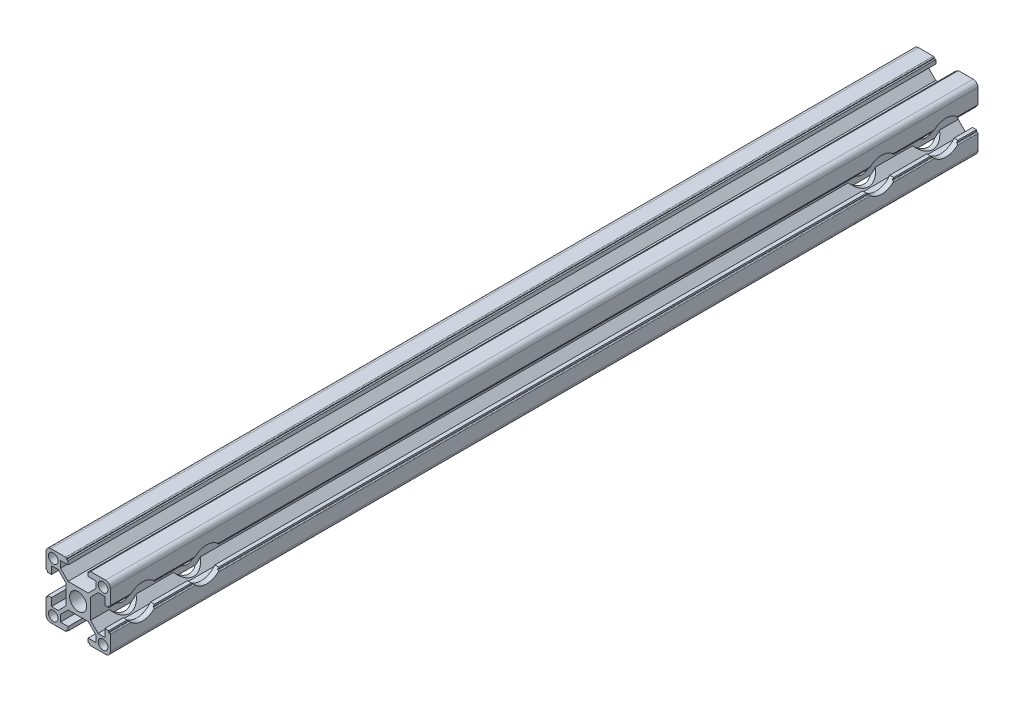
SolidWorks part; units mm, degrees
ref_plane "前视基准面" through (0, 0, 0) normal (0, 0, 1) x (1, 0, 0)
ref_plane "上视基准面" through (0, 0, 0) normal (0, 1, 0) x (1, 0, 0)
ref_plane "右视基准面" through (0, 0, 0) normal (1, 0, 0) x (0, 0, -1)
sketch "草图1" plane through (0, 0, 0) normal (0, 0, 1) x (1, 0, 0)
  line L0 (-7.75, 0) -> (0, 0) construction
  line L1 (7.75, -7.75) -> (-7.75, -7.75) construction
  line L2 (7.75, -7.75) -> (7.75, 7.75) construction
  line L3 (7.75, 7.75) -> (-7.75, 7.75) construction
  line L4 (-7.75, -7.75) -> (-7.75, 7.75) construction
  line L5 (7.75, -7.75) -> (-7.75, 7.75) construction
  line L6 (7.75, 7.75) -> (-7.75, -7.75) construction
  line L7 (0, 0) -> (0, 7.75) construction
  line L8 (3.1429, 3.85) -> (-3.1429, 3.85)
  line L9 (-3.1429, 3.85) -> (-5.5, 6.2071)
  line L10 (-5.5, 6.2071) -> (-5.5, 8.3)
  line L11 (-5.5, 8.3) -> (-3.1, 8.3)
  line L12 (-3.1, 8.3) -> (-3.1, 9.5)
  line L13 (-3.1, 9.5) -> (-3.6, 9.5)
  line L14 (-3.6, 9.5) -> (-3.6, 9.7)
  line L15 (-3.9, 10) -> (-8.5, 10)
  line L16 (-3.85, -3.1429) -> (-3.85, 3.1429)
  line L17 (-3.85, 3.1429) -> (-6.2071, 5.5)
  line L18 (-6.2071, 5.5) -> (-8.3, 5.5)
  line L19 (-8.3, 5.5) -> (-8.3, 3.1)
  line L20 (-9.5, 3.1) -> (-9.5, 3.6)
  line L21 (-8.3, 3.1) -> (-9.5, 3.1)
  line L22 (-9.5, 3.6) -> (-9.7, 3.6)
  line L23 (-10, 3.9) -> (-10, 8.5)
  line L24 (5.5, 8.3) -> (3.1, 8.3)
  line L25 (3.6, 9.5) -> (3.6, 9.7)
  line L26 (3.1, 9.5) -> (3.6, 9.5)
  line L27 (3.1, 8.3) -> (3.1, 9.5)
  line L28 (5.5, 6.2071) -> (5.5, 8.3)
  line L29 (3.1429, 3.85) -> (5.5, 6.2071)
  line L30 (3.85, -3.1429) -> (3.85, 3.1429)
  line L31 (3.85, 3.1429) -> (6.2071, 5.5)
  line L32 (9.5, 3.6) -> (9.7, 3.6)
  line L33 (8.3, 3.1) -> (9.5, 3.1)
  line L34 (9.5, 3.1) -> (9.5, 3.6)
  line L35 (8.3, 5.5) -> (8.3, 3.1)
  line L36 (6.2071, 5.5) -> (8.3, 5.5)
  line L37 (10, 3.9) -> (10, 8.5)
  line L38 (3.9, 10) -> (8.5, 10)
  line L39 (-9.5, -3.6) -> (-9.7, -3.6)
  line L40 (-8.3, -3.1) -> (-9.5, -3.1)
  line L41 (-9.5, -3.1) -> (-9.5, -3.6)
  line L42 (-8.3, -5.5) -> (-8.3, -3.1)
  line L43 (-6.2071, -5.5) -> (-8.3, -5.5)
  line L44 (-3.85, -3.1429) -> (-6.2071, -5.5)
  line L45 (-3.1429, -3.85) -> (-5.5, -6.2071)
  line L46 (-5.5, -6.2071) -> (-5.5, -8.3)
  line L47 (-3.6, -9.5) -> (-3.6, -9.7)
  line L48 (-3.1, -9.5) -> (-3.6, -9.5)
  line L49 (-3.1, -8.3) -> (-3.1, -9.5)
  line L50 (-5.5, -8.3) -> (-3.1, -8.3)
  line L51 (5.5, -6.2071) -> (5.5, -8.3)
  line L52 (3.1, -8.3) -> (3.1, -9.5)
  line L53 (3.1, -9.5) -> (3.6, -9.5)
  line L54 (3.6, -9.5) -> (3.6, -9.7)
  line L55 (5.5, -8.3) -> (3.1, -8.3)
  line L56 (3.1429, -3.85) -> (5.5, -6.2071)
  line L57 (3.1429, -3.85) -> (-3.1429, -3.85)
  line L58 (3.85, -3.1429) -> (6.2071, -5.5)
  line L59 (6.2071, -5.5) -> (8.3, -5.5)
  line L60 (8.3, -5.5) -> (8.3, -3.1)
  line L61 (9.5, -3.1) -> (9.5, -3.6)
  line L62 (8.3, -3.1) -> (9.5, -3.1)
  line L63 (9.5, -3.6) -> (9.7, -3.6)
  line L64 (3.9, -10) -> (8.5, -10)
  line L65 (10, -3.9) -> (10, -8.5)
  line L66 (-10, -3.9) -> (-10, -8.5)
  line L67 (-3.9, -10) -> (-8.5, -10)
  circle A0 centre (0, 0) radius 2.65
  circle A1 centre (-7.75, 7.75) radius 1.5
  circle A2 centre (7.75, 7.75) radius 1.5
  circle A3 centre (7.75, -7.75) radius 1.5
  circle A4 centre (-7.75, -7.75) radius 1.5
  arc A5 (-10, -8.5) -> (-8.5, -10) centre (-8.5, -8.5) ccw
  arc A6 (8.5, -10) -> (10, -8.5) centre (8.5, -8.5) ccw
  arc A7 (10, 8.5) -> (8.5, 10) centre (8.5, 8.5) ccw
  arc A8 (-8.5, 10) -> (-10, 8.5) centre (-8.5, 8.5) ccw
  arc A9 (3.6, -9.7) -> (3.9, -10) centre (3.9, -9.7) ccw
  arc A10 (-3.6, -9.7) -> (-3.9, -10) centre (-3.9, -9.7) cw
  arc A11 (-9.7, -3.6) -> (-10, -3.9) centre (-9.7, -3.9) ccw
  arc A12 (9.7, -3.6) -> (10, -3.9) centre (9.7, -3.9) cw
  arc A13 (9.7, 3.6) -> (10, 3.9) centre (9.7, 3.9) ccw
  arc A14 (-9.7, 3.6) -> (-10, 3.9) centre (-9.7, 3.9) cw
  arc A15 (3.6, 9.7) -> (3.9, 10) centre (3.9, 9.7) cw
  arc A16 (-3.6, 9.7) -> (-3.9, 10) centre (-3.9, 9.7) ccw
  point P46 (0, 3.85)
  point P56 (-3.85, 0)
  point P78 (3.85, 0)
  point P87 (-10, -10)
  point P90 (10, -10)
  point P93 (10, 10)
  point P96 (-10, 10)
  point P99 (3.6, -10)
  point P102 (-3.6, -10)
  point P105 (-10, -3.6)
  point P108 (10, -3.6)
  point P111 (10, 3.6)
  point P114 (-10, 3.6)
  point P117 (3.6, 10)
  point P120 (-3.6, 10)
  dimension "D1" = 5.3
  dimension "D2" = 3
  dimension "D11" = 1.5
  dimension "D12" = 2.25
  dimension "D13" = 0.3
  dimension "D3" = 7.7
  dimension "D4" = 6.2
  dimension "D5" = 1.7
  dimension "D6" = 1.2
  dimension "D7" = 20
  dimension "D8" = 7.2
  dimension "D9" = 11
  dimension "D10" = 1
extrude "凸台-拉伸1" add sketch "草图1" along normal mid plane 270
sketch "草图4" plane through (3.85, 0, 0) normal (1, 0, 0) x (0, 0, -1)
  line L0 (125, 0) -> (105, 0) construction
  line L2 (135, 3.9) -> (135, 8.5) construction
  line L4 (-135, -10) -> (135, -10) construction
  circle A1 centre (125, 0) radius 3.1
  circle A7 centre (105, 0) radius 3.1
  dimension "D1" = 6.2
  dimension "D2" = 10
  dimension "D3" = 20
  dimension "D4" = 10
extrude "切除-拉伸3" cut sketch "草图4" against normal through all
sketch "草图5" plane through (3.85, 0, 0) normal (1, 0, 0) x (0, 0, -1)
  circle A0 centre (105, 0) radius 5.25
  circle A1 centre (125, 0) radius 5.25
  dimension "D1" = 10.5
extrude "切除-拉伸4" cut sketch "草图5" along normal through all
sketch "草图6" plane through (3.85, 0, 0) normal (1, 0, 0) x (0, 0, -1)
  circle A0 centre (-105, 0) radius 3.1
  circle A2 centre (-125, 0) radius 3.1
  circle A3 centre (105, 0) radius 3.1 construction
  dimension "D1" = 10
  dimension "D2" = 20
extrude "切除-拉伸5" cut sketch "草图6" against normal through all
sketch "草图7" plane through (3.85, 0, 0) normal (1, 0, 0) x (0, 0, -1)
  circle A0 centre (-105, 0) radius 5.25
  circle A2 centre (-125, 0) radius 5.25
  dimension "D1" = 10.5
extrude "切除-拉伸6" cut sketch "草图7" along normal through all
